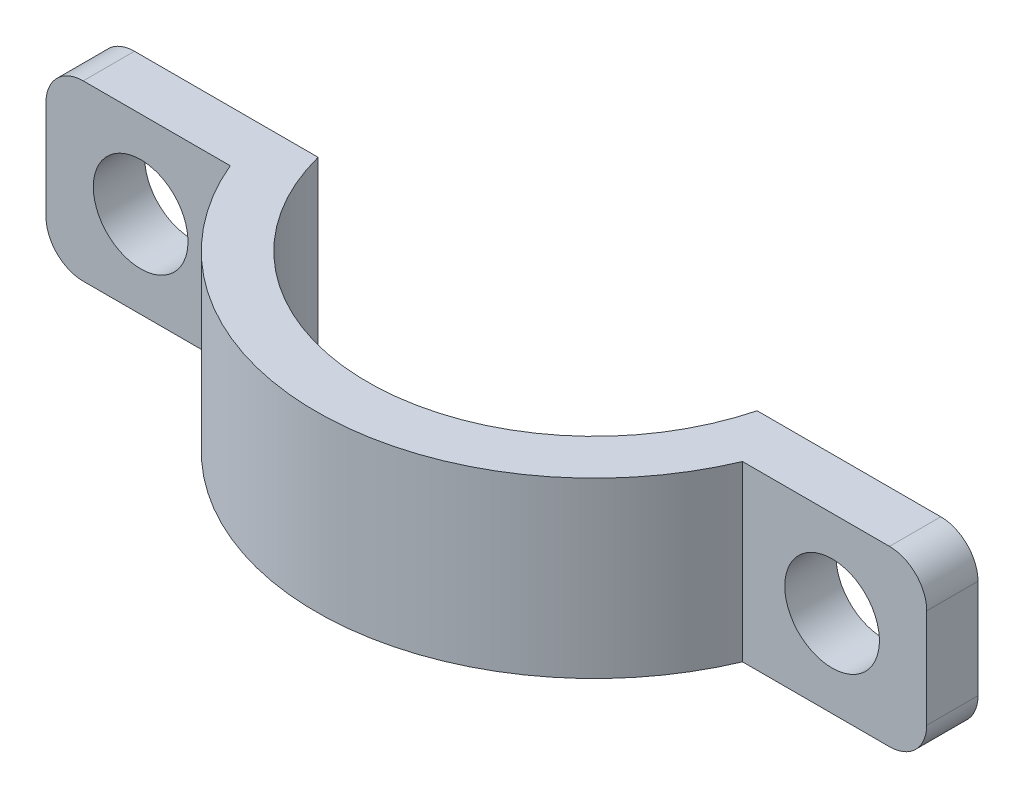
SolidWorks part; units mm, degrees
material "6061-T6 (SS)"
ref_plane "Front Plane" through (0, 0, 0) normal (0, 0, 1) x (1, 0, 0)
ref_plane "Top Plane" through (0, 0, 0) normal (0, 1, 0) x (1, 0, 0)
ref_plane "Right Plane" through (0, 0, 0) normal (1, 0, 0) x (0, 0, -1)
sketch "Sketch1" plane through (0, 0, 0) normal (0, 1, 0) x (1, 0, 0)
  line L0 (-27.9162, -22.7194) -> (27.9162, -22.7194)
  line L2 (-27.9162, -22.7194) -> (-27.9162, -3.6027)
  line L3 (-27.9162, -3.6027) -> (-13.9162, -3.6027)
  line L4 (27.9162, -22.7194) -> (27.9162, -3.6027)
  line L5 (-21.6243, -22.7194) -> (27.9162, -3.6027) construction
  line L6 (-27.9162, -3.6027) -> (21.6243, -22.7194) construction
  line L7 (13.9162, -3.6027) -> (27.9162, -3.6027)
  arc A0 (-13.9162, -3.6027) -> (13.9162, -3.6027) centre (0, 0) ccw
  point P3 (0, -14.375)
  dimension "D1" = 28.75
  dimension "D2" = 14
  dimension "D3" = 14
extrude "Boss-Extrude1" add sketch "Sketch1" along normal blind 11
sketch "Sketch2" plane through (0, 0, 3.6027) normal (0, 0, -1) x (-1, 0, 0)
  line L0 (21.9162, 5.5) -> (27.9162, 5.5) construction
  line L2 (27.9162, 11) -> (27.9162, 0) construction
  line L4 (-21.9162, 5.5) -> (-27.9162, 5.5) construction
  line L8 (-27.9162, 11) -> (-27.9162, 0) construction
  line L9 (-27.9162, 5.5) -> (-27.9162, 0) construction
  circle A0 centre (21.9162, 5.5) radius 3
  circle A1 centre (-21.9162, 5.5) radius 3
extrude "Cut-Extrude1" cut sketch "Sketch2" against normal blind 30
sketch "Sketch4" plane through (0, 0, 0) normal (0, -1, 0) x (1, 0, 0)
  line L6 (27.9162, 6.8527) -> (27.9162, 7.6027)
  line L7 (-27.9162, 7.6027) -> (-27.9162, 6.8527)
  line L8 (27.9162, 6.8527) -> (16.2383, 6.8527)
  line L9 (-16.2383, 6.8527) -> (-27.9162, 6.8527)
  line L10 (-27.9162, 7.6027) -> (-27.9162, 22.7194)
  line L11 (-27.9162, 22.7194) -> (27.9162, 22.7194)
  line L12 (27.9162, 22.7194) -> (27.9162, 7.6027)
  line L13 (27.9162, 6.8527) -> (16.2383, 6.8527)
  line L14 (-16.2383, 6.8527) -> (-27.9162, 6.8527)
  arc A4 (16.2383, 6.8527) -> (-16.2383, 6.8527) centre (0, 0) ccw
  arc A5 (16.2383, 6.8527) -> (-16.2383, 6.8527) centre (0, 0) ccw
  dimension "D1" = 3.25
extrude "Cut-Extrude2" cut sketch "Sketch4" against normal blind 20
fillet "Fillet1" radius 2.36 4 edges at (27.9162, 0, 5.2277) (27.9162, 11, 5.2277) (-27.9162, 11, 5.2277) (-27.9162, 0, 5.2277)
